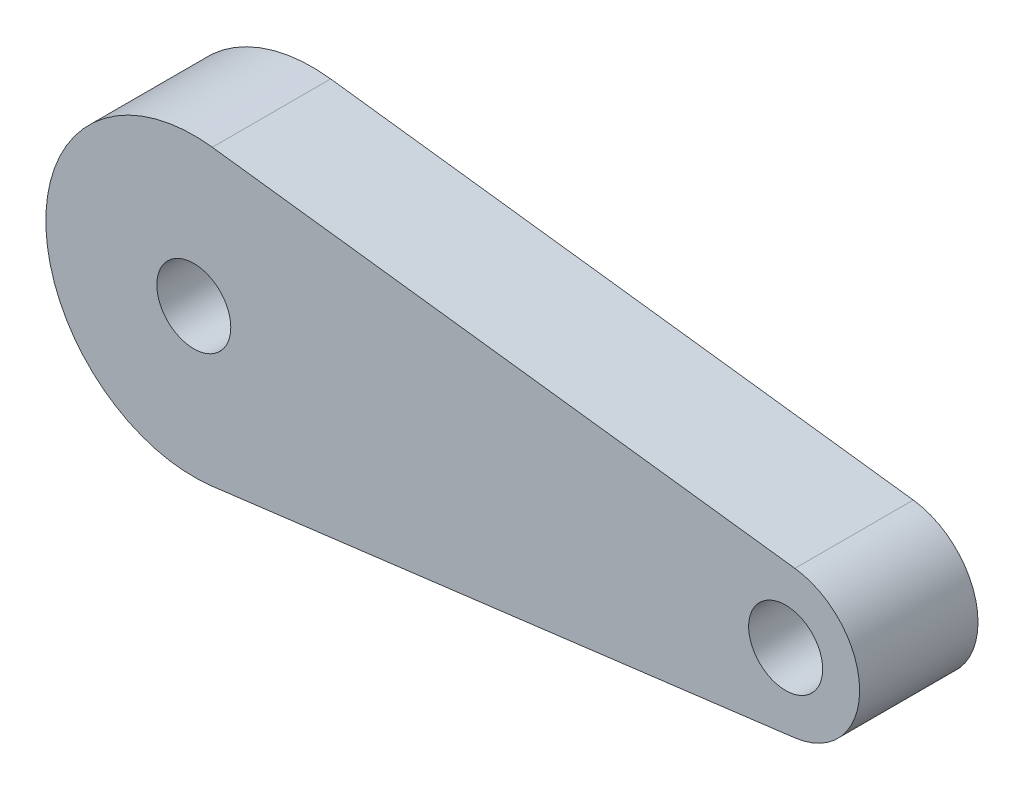
SolidWorks part; units mm, degrees
material "6061 合金"
ref_plane "前视基准面" through (0, 0, 0) normal (0, 0, 1) x (1, 0, 0)
ref_plane "上视基准面" through (0, 0, 0) normal (0, 1, 0) x (1, 0, 0)
ref_plane "右视基准面" through (0, 0, 0) normal (1, 0, 0) x (0, 0, -1)
other "Configuration Table"
sketch "草图2" plane through (0, 0, 0) normal (0, 0, 1) x (1, 0, 0)
  line L0 (1.25, 9.9216) -> (40.625, 4.9608)
  line L1 (1.25, -9.9216) -> (40.625, -4.9608)
  line L2 (0, 0) -> (49.411, 0) construction
  circle A0 centre (0, 0) radius 10
  circle A1 centre (40, 0) radius 5
  circle A2 centre (40, 0) radius 2.5
  circle A3 centre (0, 0) radius 2.5
  dimension "D1" = 20
  dimension "D2" = 10
  dimension "D3" = 40
  dimension "D4" = 5
  dimension "D5" = 5
extrude "凸台-拉伸1" add sketch "草图2" along normal blind 8 contours A0 A3 | A1 L0 A0 L1 | A1 A2 | L2 A1 A2 | L2 A0 L1 A1
